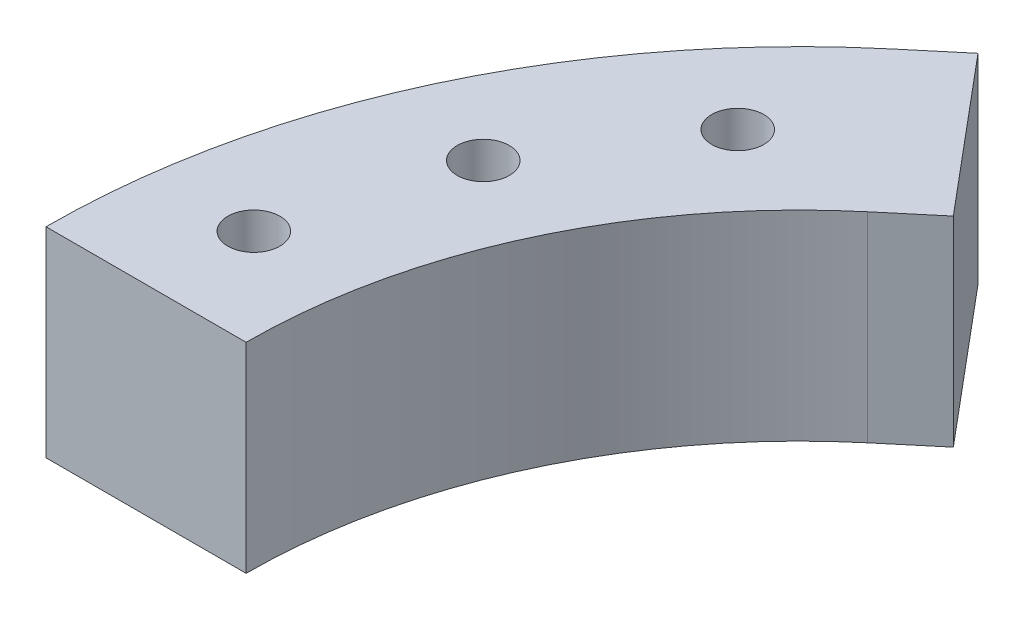
SolidWorks part; units mm, degrees
material "Custom Plastic"
ref_plane "Front Plane" through (0, 0, 0) normal (0, 0, 1) x (1, 0, 0)
ref_plane "Top Plane" through (0, 0, 0) normal (0, 1, 0) x (1, 0, 0)
ref_plane "Right Plane" through (0, 0, 0) normal (1, 0, 0) x (0, 0, -1)
sketch "Sketch1" plane through (0, 0, 0) normal (0, 1, 0) x (1, 0, 0)
  line L0 (0, 0) -> (77.7862, 0) construction
  line L1 (77.7862, 0) -> (77.7862, 50) construction
  line L2 (0, 0) -> (0, -10) construction
  line L3 (23.3154, 50) -> (-36.2723, 0) construction
  line L4 (10, 0) -> (-10, 0)
  line L5 (29.7433, 42.3396) -> (16.8875, 57.6604)
  arc A0 (0, 0) -> (23.3154, 50) centre (65.2704, 0) cw construction
  arc A1 (10, 0) -> (29.7433, 42.3396) centre (65.2704, 0) cw
  arc A2 (-10, 0) -> (16.8875, 57.6604) centre (65.2704, 0) cw
  circle A3 centre (0.7706, 10) radius 2.6
  circle A4 centre (6.1153, 27.5844) radius 2.6
  circle A5 centre (16.1503, 42.9818) radius 2.6
  circle A7 centre (30.0798, 54.9713) radius 2.6 [skipped]
  point P24 (65.2704, 0)
  dimension "D6" = 5.2
  dimension "D9" = 10
  dimension "D1" = 10
  dimension "D2" = 40
  dimension "D3" = 50
  dimension "D7" = 10
  dimension "D8" = 4
  dimension "D4" = 10
  dimension "D5" = 10
extrude "Boss-Extrude1" add sketch "Sketch1" along normal blind 20
sketch "Sketch2" plane through (0, 20, 0) normal (0, 1, 0) x (1, 0, 0)
  line L0 (16.8875, 57.6604) -> (29.7433, 42.3396)
  line L1 (16.8875, 57.6604) -> (21.5604, 61.5814)
  line L2 (29.7433, 42.3396) -> (34.4161, 46.2606)
  line L3 (21.5604, 61.5814) -> (34.4161, 46.2606)
  dimension "D1" = 6.1
extrude "Boss-Extrude2" add sketch "Sketch2" against normal up to surface (20 mm away) up to face at (0.7706, 0, -7.4)
